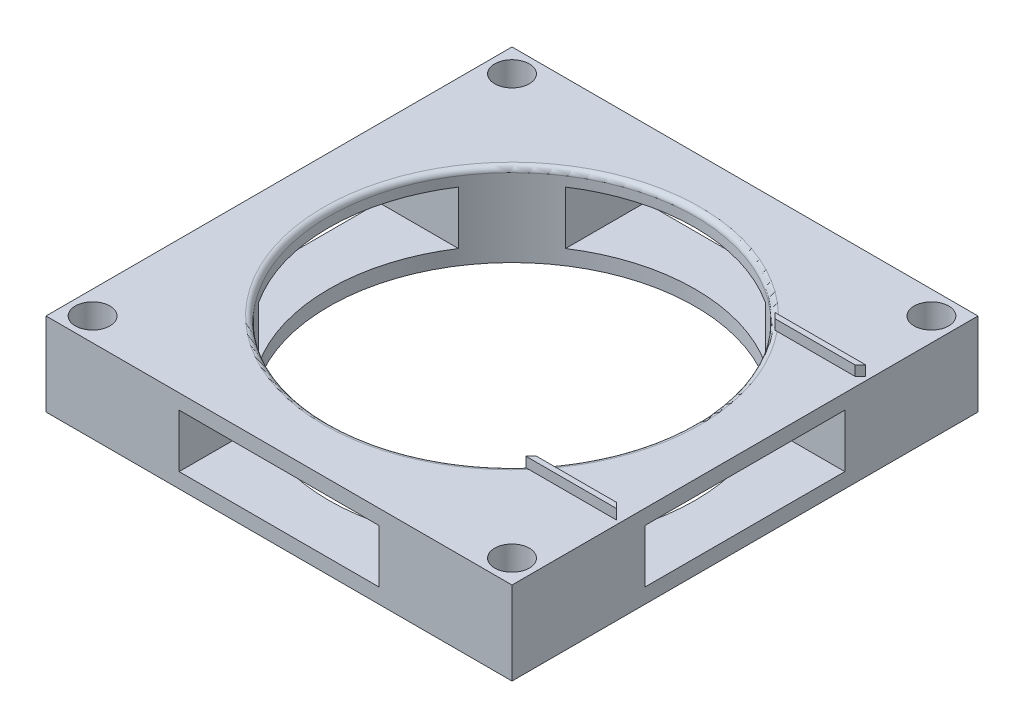
SolidWorks part; units mm, degrees
ref_plane "Front Plane" through (0, 0, 0) normal (0, 0, 1) x (1, 0, 0)
ref_plane "Top Plane" through (0, 0, 0) normal (0, 1, 0) x (1, 0, 0)
ref_plane "Right Plane" through (0, 0, 0) normal (1, 0, 0) x (0, 0, -1)
sketch "Sketch1" plane through (0, 0, 0) normal (0, 1, 0) x (1, 0, 0)
  line L0 (0, 35) -> (0, -35) construction
  line L1 (35, 35) -> (-35, 35)
  line L2 (35, 35) -> (35, -35)
  line L3 (35, -35) -> (-35, -35)
  line L4 (-35, 35) -> (-35, -35)
  line L5 (35, 35) -> (-35, -35) construction
  line L6 (35, -35) -> (-35, 35) construction
  line L7 (-35, 0) -> (35, 0) construction
  circle A0 centre (-31.5, 31.5) radius 2.6
  circle A1 centre (31.5, 31.5) radius 2.6
  circle A2 centre (31.5, -31.5) radius 2.6
  circle A3 centre (-31.5, -31.5) radius 2.6
  point P0 (0, 0)
  dimension "D3" = 5.2
  dimension "D1" = 70
  dimension "D2" = 70
  dimension "D4" = 3.5
  dimension "D5" = 3.5
extrude "Boss-Extrude1" add sketch "Sketch1" along normal blind 12.5 contours L1 L4 L3 L2 A1 A0 A2 A3
sketch "Sketch2" plane through (0, 12.5, 0) normal (0, 1, 0) x (1, 0, 0)
  line L0 (0, 35) -> (0, -35) construction
  line L1 (35, 35) -> (-35, 35) construction
  line L2 (35, -35) -> (-35, -35) construction
  line L3 (-35, 0) -> (35, 0) construction
  line L4 (-35, 35) -> (-35, -35) construction
  line L5 (35, 35) -> (35, -35) construction
  circle A0 centre (0, 0) radius 27.5
  dimension "D1" = 55
extrude "Cut-Extrude1" cut sketch "Sketch2" against normal blind 14
fillet "Fillet1" radius 0.8 1 edges at (0, 12.5, 27.5)
sketch "Sketch3" plane through (0, 12.5, 0) normal (0, 1, 0) x (1, 0, 0)
  line L1 (33.6, 17.9) -> (21.6, 17.9)
  line L3 (33.6, -17.9) -> (21.6, -17.9)
  line L5 (33.6, 17.9) -> (21.6, -17.9) construction
  line L6 (33.6, -17.9) -> (21.6, 17.9) construction
  line L7 (34.4, -18.7) -> (20.8, -18.7)
  line L9 (34.4, 18.7) -> (20.8, 18.7)
  line L10 (33.6, 17.9) -> (33.6, -17.9) construction
  line L11 (34.4, 18.7) -> (34.4, -18.7) construction
  line L12 (34.4, 18.7) -> (33.6, 17.9)
  line L13 (33.6, -17.9) -> (34.4, -18.7)
  line L14 (20.8, 18.7) -> (21.6, 17.9)
  line L15 (20.8, -18.7) -> (21.6, -17.9)
  line L16 (35, 35) -> (35, -35) construction
  line L17 (20.8, 18.7) -> (20.8, -18.7) construction
  line L18 (21.6, 17.9) -> (21.6, -17.9) construction
  dimension "D1" = 35.8
  dimension "D2" = 12
  dimension "D4" = 1.4
  dimension "D5" = 12
  dimension "D3" = 0.8
extrude "Boss-Extrude2" add sketch "Sketch3" along normal blind 1.5
sketch "Sketch4" plane through (0, 14, 0) normal (0, 1, 0) x (1, 0, 0)
  line L0 (34.4, -18.7) -> (33.6, -17.9) construction
  line L1 (21.6, -17.9) -> (20.8, -18.7) construction
  line L2 (20.8, -18.7) -> (34.4, -18.7) construction
  line L3 (33.6, -17.9) -> (21.6, -17.9) construction
  line L4 (20.8, 18.7) -> (21.6, 17.9)
  line L5 (21.6, 17.9) -> (33.6, 17.9)
  line L6 (33.6, 17.9) -> (34.4, 18.7)
  line L7 (34.4, 18.7) -> (20.8, 18.7)
  line L8 (20.8, 18.7) -> (21.6, 17.9)
  line L9 (21.6, 17.9) -> (33.6, 17.9)
  line L10 (33.6, 17.9) -> (34.4, 18.7)
  line L11 (34.4, 18.7) -> (20.8, 18.7)
  line L12 (34.4, -18.7) -> (33.6, -17.9)
  line L13 (21.6, -17.9) -> (20.8, -18.7)
  line L14 (20.8, -18.7) -> (34.4, -18.7)
  line L15 (33.6, -17.9) -> (21.6, -17.9)
  line L16 (21.6, 17.9) -> (21.6, -17.9)
  line L17 (33.6, 17.9) -> (33.6, -17.9)
  dimension "D1" = 0
sketch "Sketch5" plane through (0, 0, 35) normal (0, 0, 1) x (1, 0, 0)
  line L0 (35, 12.5) -> (-35, 12.5) construction
  line L1 (15, 2.25) -> (-15, 2.25)
  line L2 (15, 2.25) -> (15, 10.25)
  line L3 (15, 10.25) -> (-15, 10.25)
  line L4 (-15, 2.25) -> (-15, 10.25)
  line L5 (15, 2.25) -> (-15, 10.25) construction
  line L6 (15, 10.25) -> (-15, 2.25) construction
  line L7 (0, 0) -> (0, 12.5) construction
  line L8 (35, 0) -> (-35, 0) construction
  point P0 (0, 6.25)
  point P7 (0, 0)
  dimension "D1" = 30
  dimension "D2" = 8
extrude "Cut-Extrude2" cut sketch "Sketch5" against normal through all
sketch "Sketch6" plane through (35, 0, 0) normal (1, 0, 0) x (0, 0, -1)
  line L0 (0, 0) -> (0, 12.5) construction
  line L1 (35, 12.5) -> (-35, 12.5) construction
  line L3 (15, 10.25) -> (-15, 10.25)
  line L4 (15, 10.25) -> (15, 2.25)
  line L5 (15, 2.25) -> (-15, 2.25)
  line L6 (-15, 10.25) -> (-15, 2.25)
  line L7 (15, 10.25) -> (-15, 2.25) construction
  line L8 (15, 2.25) -> (-15, 10.25) construction
  point P5 (0, 6.25)
  dimension "D1" = 30
  dimension "D2" = 8
extrude "Cut-Extrude3" cut sketch "Sketch6" against normal through all
